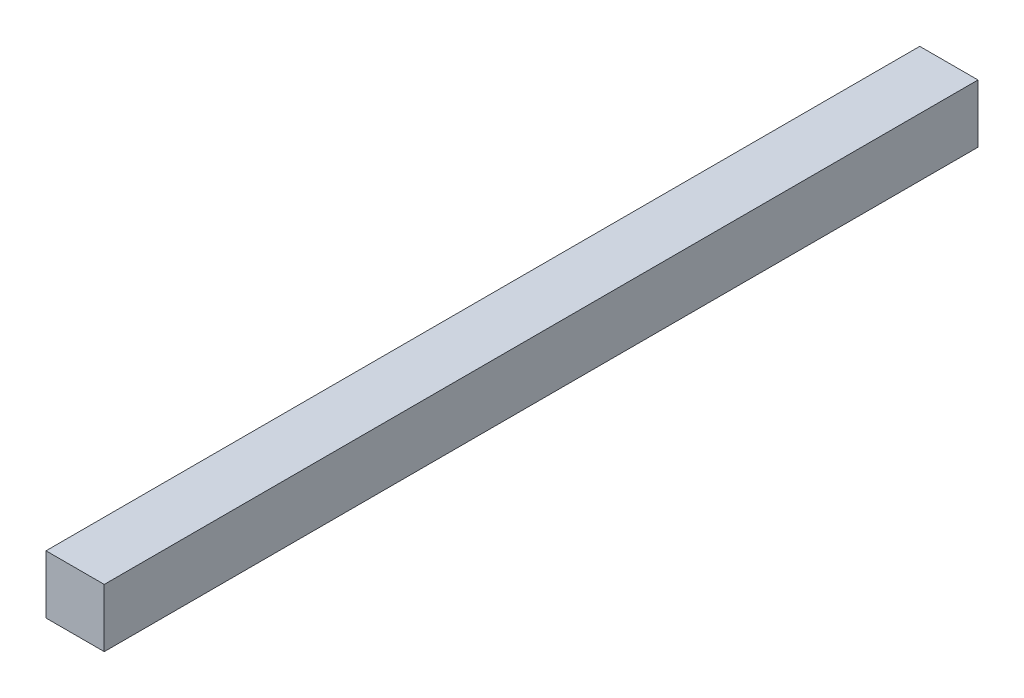
SolidWorks part; units mm, degrees
ref_plane "Спереди" through (0, 0, 0) normal (0, 0, 1) x (1, 0, 0)
ref_plane "Сверху" through (0, 0, 0) normal (0, 1, 0) x (1, 0, 0)
ref_plane "Справа" through (0, 0, 0) normal (1, 0, 0) x (0, 0, -1)
sketch "Эскиз1" plane through (0, 0, 0) normal (0, 0, 1) x (1, 0, 0)
  line L1 (0, 0) -> (20, 0)
  line L2 (0, 0) -> (0, 20)
  line L3 (0, 20) -> (20, 20)
  line L4 (20, 0) -> (20, 20)
  dimension "D1" = 20
  dimension "D2" = 20
extrude "Бобышка-Вытянуть1" add sketch "Эскиз1" along normal blind 300
